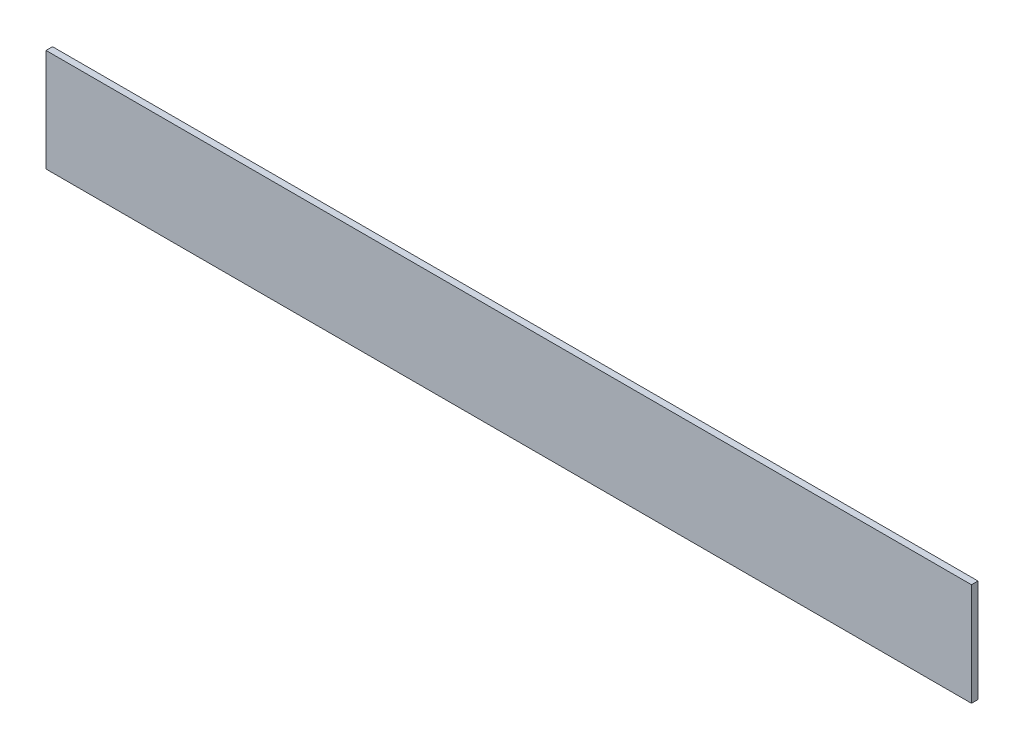
SolidWorks part; units mm, degrees
material "6061-T6 (SS)"
ref_plane "X-Y Datum" through (0, 0, 0) normal (0, 0, 1) x (1, 0, 0)
ref_plane "X-Z Datum" through (0, 0, 0) normal (0, 1, 0) x (1, 0, 0)
ref_plane "Y-Z Datum" through (0, 0, 0) normal (1, 0, 0) x (0, 0, -1)
sketch "Sketch1" plane through (0, 0, 0) normal (0, 0, 1) x (1, 0, 0)
  line L1 (-225.435, -25.019) -> (225.435, -25.019)
  line L2 (-225.435, -25.019) -> (-225.435, 25.019)
  line L3 (-225.435, 25.019) -> (225.435, 25.019)
  line L4 (225.435, -25.019) -> (225.435, 25.019)
  line L5 (-225.435, -25.019) -> (225.435, 25.019) construction
  line L6 (-225.435, 25.019) -> (225.435, -25.019) construction
  point P0 (0, 0)
  dimension "D1" = 450.87
  dimension "D2" = 50.038
extrude "Boss-Extrude1" add sketch "Sketch1" along normal blind 3.175
